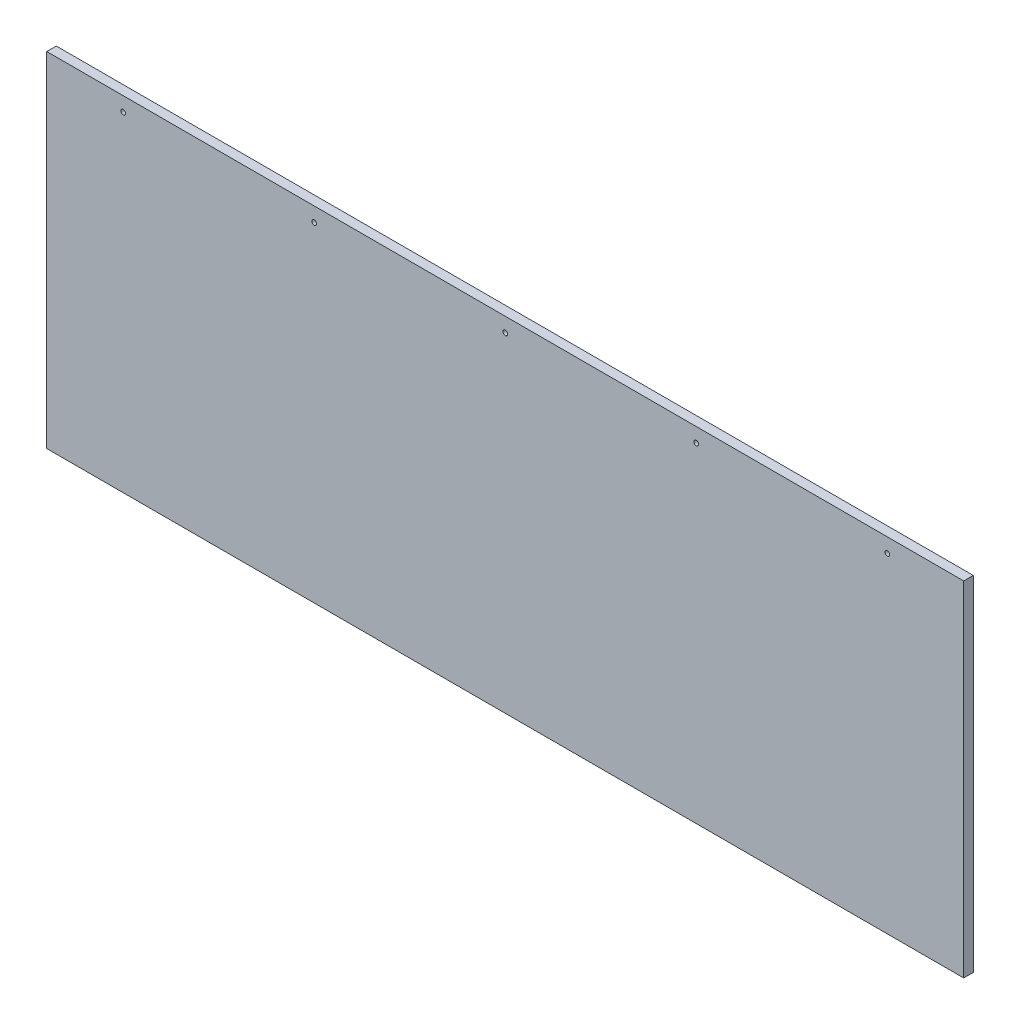
SolidWorks part; units mm, degrees
ref_plane "Front" through (0, 0, 0) normal (0, 0, 1) x (1, 0, 0)
ref_plane "Top" through (0, 0, 0) normal (0, 1, 0) x (1, 0, 0)
ref_plane "Right" through (0, 0, 0) normal (1, 0, 0) x (0, 0, -1)
sketch "Sketch1" plane through (0, 0, 0) normal (0, 0, 1) x (1, 0, 0)
  line L1 (0, 0) -> (-1219.2, 0)
  line L2 (0, 0) -> (0, 457.2)
  line L3 (0, 457.2) -> (-1219.2, 457.2)
  line L4 (-1219.2, 0) -> (-1219.2, 457.2)
  dimension "D1" = 457.2
  dimension "D2" = 1219.2
extrude "Boss-Extrude1" add sketch "Sketch1" along normal blind 12.7
sketch "Sketch2"
  circle A0 centre (-1117.6, 438.15) radius 3.175
  circle A1 centre (-863.6, 438.15) radius 3.175
  circle A2 centre (-609.6, 438.15) radius 3.175
  circle A3 centre (-355.6, 438.15) radius 3.175
  circle A4 centre (-101.6, 438.15) radius 3.175
other "AlignGroup1" parameters "D1"=39.1704, "D2"=0, "D3"=438.15, "D4"=0, "D5"=101.6, "D6"=355.6, "D7"=609.6, "D8"=863.6, "D9"=1117.6
other "AlignGroup2"
extrude "Cut-Extrude1" cut sketch "Sketch2" against normal through all
